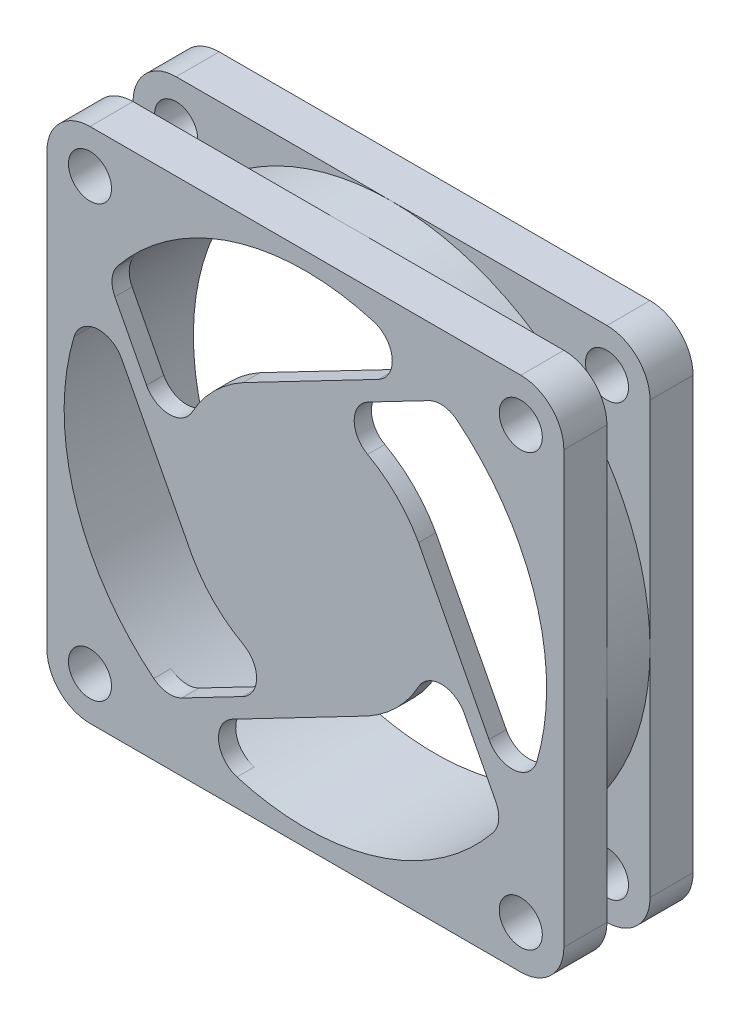
SolidWorks part; units mm, degrees
ref_plane "Front Plane" through (0, 0, 0) normal (0, 0, 1) x (1, 0, 0)
ref_plane "Top Plane" through (0, 0, 0) normal (0, 1, 0) x (1, 0, 0)
ref_plane "Right Plane" through (0, 0, 0) normal (1, 0, 0) x (0, 0, -1)
sketch "Sketch1" plane through (0, 0, 0) normal (0, 0, 1) x (1, 0, 0)
  line L1 (-30, -30) -> (30, -30)
  line L2 (-30, -30) -> (-30, 30)
  line L3 (-30, 30) -> (30, 30)
  line L4 (30, -30) -> (30, 30)
  line L5 (-30, -30) -> (30, 30) construction
  line L6 (-30, 30) -> (30, -30) construction
  circle A0 centre (0, 0) radius 28
  circle A1 centre (25, 25) radius 2.5
  circle A2 centre (-25, 25) radius 2.5
  circle A3 centre (-25, -25) radius 2.5
  circle A4 centre (25, -25) radius 2.5
  point P0 (0, 0)
  dimension "D3" = 56
  dimension "D4" = 5
  dimension "D5" = 5
  dimension "D6" = 5
  dimension "D7" = 5
  dimension "D8" = 5
  dimension "D1" = 60
  dimension "D2" = 60
extrude "Boss-Extrude1" add sketch "Sketch1" along normal mid plane 15
sketch "Sketch2" plane through (0, 0, 0) normal (0, 0, 1) x (1, 0, 0)
  line L1 (-41.7112, -39.8986) -> (41.7112, -39.8986)
  line L2 (-41.7112, -39.8986) -> (-41.7112, 39.8986)
  line L3 (-41.7112, 39.8986) -> (41.7112, 39.8986)
  line L4 (41.7112, -39.8986) -> (41.7112, 39.8986)
  line L5 (-41.7112, -39.8986) -> (41.7112, 39.8986) construction
  line L6 (-41.7112, 39.8986) -> (41.7112, -39.8986) construction
  circle A0 centre (0, 0) radius 30
  point P0 (0, 0)
  dimension "D1" = 60
extrude "Cut-Extrude1" cut sketch "Sketch2" against normal mid plane 5
sketch "Sketch3" plane through (0, 0, 7.5) normal (0, 0, 1) x (1, 0, 0)
  line L0 (22.9783, -16) -> (14.9861, -0.6445)
  line L1 (24.2188, -14.0516) -> (13.1385, 7.2375)
  line L2 (16, 22.9783) -> (0.6445, 14.9861)
  line L3 (14.0516, 24.2188) -> (-7.2375, 13.1385)
  line L4 (-16, -22.9783) -> (-0.6445, -14.9861)
  line L5 (-14.0516, -24.2188) -> (7.2375, -13.1385)
  line L6 (-22.9783, 16) -> (-14.9861, 0.6445)
  line L7 (-24.2188, 14.0516) -> (-13.1385, -7.2375)
  arc A0 (-7.2375, 13.1385) -> (-14.9861, 0.6445) centre (0, 0) ccw
  circle A1 centre (0, 0) radius 28 construction
  arc A2 (-13.4655, -6.6092) -> (-0.6445, -14.9861) centre (0, 0) ccw
  arc A3 (6.6092, -13.4655) -> (14.9861, -0.6445) centre (0, 0) ccw
  arc A4 (13.4655, 6.6092) -> (0.6445, 14.9861) centre (0, 0) ccw
  arc A5 (-22.9783, 16) -> (-24.2188, 14.0516) centre (0, 0) ccw
  arc A6 (16, 22.9783) -> (14.0516, 24.2188) centre (0, 0) ccw
  arc A7 (-16, -22.9783) -> (-14.0516, -24.2188) centre (0, 0) ccw
  arc A8 (22.9783, -16) -> (24.2188, -14.0516) centre (0, 0) ccw
  point P24 (0, 0)
  circle M7 centre (0, 0) radius 28
  dimension "D1" = 30
  dimension "D2" = 2
  dimension "D3" = 24
  dimension "D4" = 14
  dimension "D5" = 4
extrude "Boss-Extrude2" add sketch "Sketch3" against normal blind 2 contours L1 A4 L2 L3 A0 L6 L7 A2 L4 L5 A3 L0 M7
fillet "Fillet1" radius 3 12 edges at (14.9861, -0.6445, 6.5) (24.2188, -14.0516, 6.5) (22.9783, -16, 6.5) (-0.6445, -14.9861, 6.5) (-14.0516, -24.2188, 6.5) (-16, -22.9783, 6.5) (-14.9861, 0.6445, 6.5) (-24.2188, 14.0516, 6.5) (-22.9783, 16, 6.5) (16, 22.9783, 6.5) (0.6445, 14.9861, 6.5) (14.0516, 24.2188, 6.5)
fillet "Fillet2" radius 5 8 edges at (-30, -30, 5) (-30, -30, -5) (30, -30, -5) (30, -30, 5) (-30, 30, 5) (-30, 30, -5) (30, 30, 5) (30, 30, -5)
